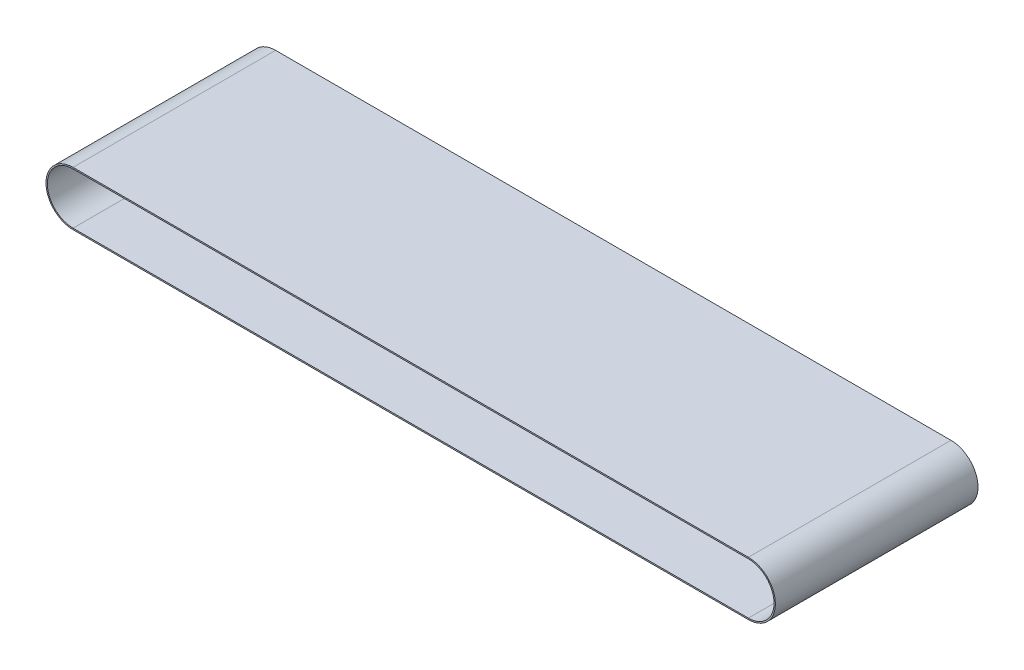
SolidWorks part; units mm, degrees
material "PVC皮带 0.007 塑化"
ref_plane "前视基准面" through (0, 0, 0) normal (0, 0, 1) x (1, 0, 0)
ref_plane "上视基准面" through (0, 0, 0) normal (0, 1, 0) x (1, 0, 0)
ref_plane "右视基准面" through (0, 0, 0) normal (1, 0, 0) x (0, 0, -1)
sketch "草图1" plane through (0, 0, 0) normal (0, 0, 1) x (1, 0, 0)
  line L0 (-500, 0) -> (500, 0) construction
  line L1 (-500, 38) -> (500, 38)
  line L2 (-500, -38) -> (500, -38)
  arc A0 (-500, 38) -> (-500, -38) centre (-500, 0) ccw
  arc A1 (500, -38) -> (500, 38) centre (500, 0) ccw
  point P2 (0, 0)
  dimension "D2" = 76
  dimension "D1" = 1000
extrude "拉伸-薄壁1" add sketch "草图1" along normal mid plane 300 thin thin type one direction wall 2
